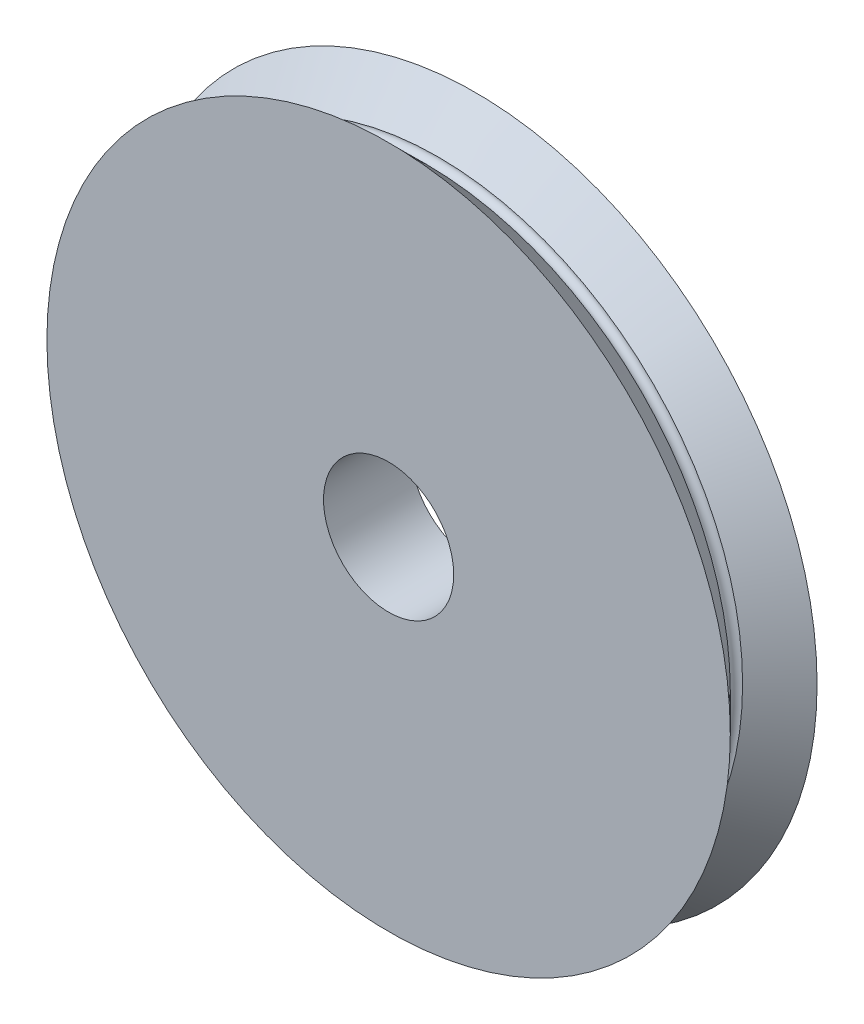
SolidWorks part; units mm, degrees
ref_plane "Front Plane" through (0, 0, 0) normal (0, 0, 1) x (1, 0, 0)
ref_plane "Top Plane" through (0, 0, 0) normal (0, 1, 0) x (1, 0, 0)
ref_plane "Right Plane" through (0, 0, 0) normal (1, 0, 0) x (0, 0, -1)
sketch "Sketch1" plane through (0, 0, 0) normal (0, 1, 0) x (1, 0, 0)
  line L0 (9.525, 0) -> (9.525, 12.7)
  line L1 (9.525, 12.7) -> (50, 12.7)
  line L2 (50, 12.7) -> (44.55, 7.25)
  line L3 (44.55, 5.45) -> (50, 0)
  line L4 (50, 0) -> (9.525, 0)
  line L5 (0, 0) -> (0, 12.7) construction
  arc A0 (44.55, 7.25) -> (44.55, 5.45) centre (44.55, 6.35) ccw
  point P10 (9.525, 6.35)
  dimension "D3" = 0.9
  dimension "D1" = 45
  dimension "D2" = 12.7
  dimension "D4" = 100
  dimension "D5" = 19.05
revolve "Revolve1" add sketch "Sketch1" angle 360 about L5
